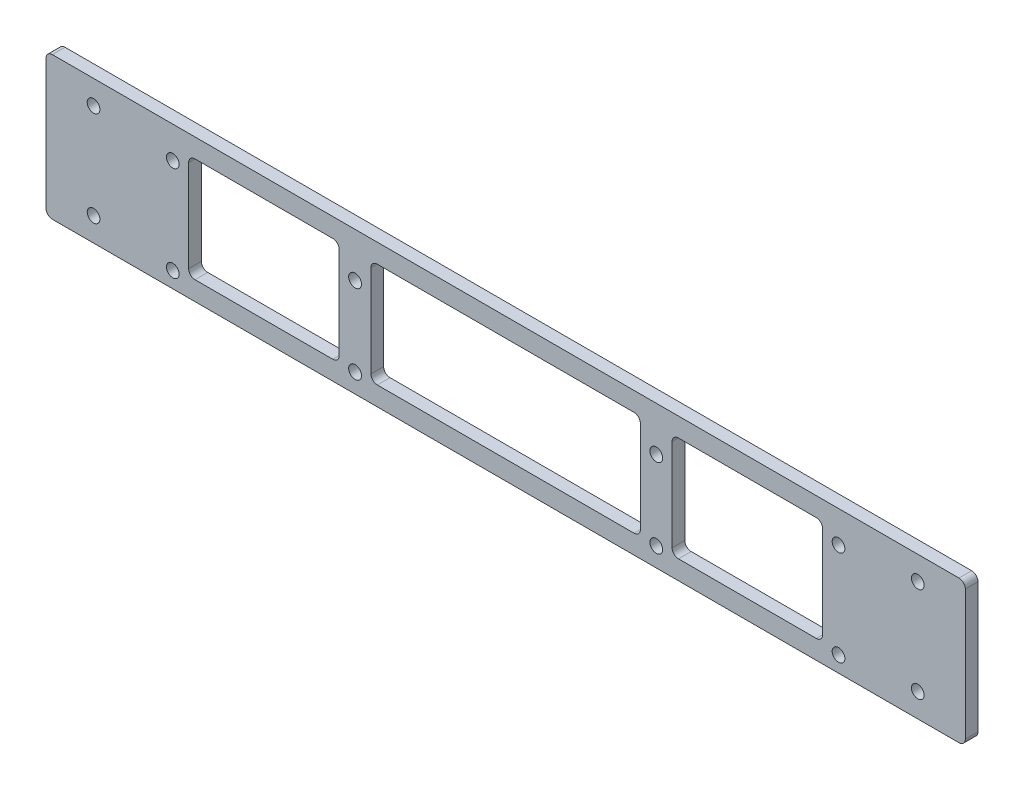
SolidWorks part; units mm, degrees
material "Thornel Mat VMA"
ref_plane "前视基准面" through (0, 0, 0) normal (0, 0, 1) x (1, 0, 0)
ref_plane "上视基准面" through (0, 0, 0) normal (0, 1, 0) x (1, 0, 0)
ref_plane "右视基准面" through (0, 0, 0) normal (1, 0, 0) x (0, 0, -1)
sketch "草图1" plane through (0, 0, 0) normal (0, 0, 1) x (1, 0, 0)
  line L1 (-145, -22.5) -> (145, -22.5)
  line L2 (-145, -22.5) -> (-145, 22.5)
  line L3 (-145, 22.5) -> (145, 22.5)
  line L4 (145, -22.5) -> (145, 22.5)
  line L5 (0, 22.5) -> (0, -22.5) construction
  line L6 (-145, 0) -> (145, 0) construction
  point P0 (0, 0)
  dimension "D1" = 45
  dimension "D2" = 290
extrude "凸台-拉伸1" add sketch "草图1" along normal mid plane 4
sketch "草图3" plane through (0, 0, -2) normal (0, 0, -1) x (-1, 0, 0)
  circle A0 centre (-47.5, 8.5243) radius 1.65 construction
  circle A1 centre (-47.5, -16.4757) radius 1.65 construction
  circle A2 centre (47.5, 8.5243) radius 1.65 construction
  circle A3 centre (47.5, -16.4757) radius 1.65 construction
  circle A4 centre (-47.5, 8.5243) radius 1.65 construction
  circle A5 centre (-47.5, -16.4757) radius 1.65 construction
  circle A6 centre (47.5, 8.5243) radius 1.65 construction
  circle A7 centre (47.5, -16.4757) radius 1.65 construction
  circle A8 centre (-47.5, 8.5243) radius 2.025
  circle A9 centre (-47.5, -16.4757) radius 2.025
  circle A10 centre (47.5, 8.5243) radius 2.025
  circle A11 centre (47.5, -16.4757) radius 2.025
  dimension "D1" = 4.05
extrude "切除-拉伸1" cut sketch "草图3" against normal blind 10
sketch "草图4" plane through (0, 0, -2) normal (0, 0, -1) x (-1, 0, 0)
  line L0 (-130, 22.5) -> (-130, -22.5) construction
  line L1 (-145, 22.5) -> (145, 22.5) construction
  line L2 (145, -22.5) -> (-145, -22.5) construction
  line L3 (-145, -22.5) -> (-145, 22.5) construction
  line L4 (-130, 0) -> (-98.4237, 0) construction
  circle A0 centre (-130, 15) radius 2
  circle A1 centre (-130, -15) radius 2
  dimension "D2" = 4
  dimension "D1" = 15
  dimension "D3" = 30
extrude "切除-拉伸2" cut sketch "草图4" against normal blind 10
mirror "镜向1" about plane through (0, 0, 0) normal (1, 0, 0) of "切除-拉伸2"
sketch "草图5" plane through (0, 0, -2) normal (0, 0, -1) x (-1, 0, 0)
  circle A0 centre (-105, -17.5) radius 2 construction
  circle A1 centre (-105, 12.5) radius 2 construction
  circle A2 centre (-105, -17.5) radius 2
  circle A3 centre (-105, 12.5) radius 2
extrude "切除-拉伸3" cut sketch "草图5" against normal mid plane 70
mirror "镜向2" about plane through (0, 0, 0) normal (1, 0, 0) of "切除-拉伸3"
sketch "草图6" plane through (0, 0, -2) normal (0, 0, -1) x (-1, 0, 0)
  line L0 (-76.25, 0) -> (0, 0) construction
  line L1 (-100, -16.5) -> (-52.5, -16.5)
  line L2 (-100, -16.5) -> (-100, 16.5)
  line L3 (-100, 16.5) -> (-52.5, 16.5)
  line L4 (-52.5, -16.5) -> (-52.5, 16.5)
  line L5 (-76.25, 16.5) -> (-76.25, -16.5) construction
  line L6 (-100, 0) -> (-52.5, 0) construction
  line L7 (145, -22.5) -> (-145, -22.5) construction
  circle A0 centre (-47.5, 8.5243) radius 2.025 construction
  circle A1 centre (-105, 12.5) radius 2 construction
  point P0 (-76.25, 0)
  dimension "D2" = 5
  dimension "D1" = 5
  dimension "D3" = 6
extrude "切除-拉伸4" cut sketch "草图6" against normal mid plane 259
mirror "镜向3" about plane through (0, 0, 0) normal (1, 0, 0) of "切除-拉伸4"
sketch "草图7" plane through (0, 0, -2) normal (0, 0, -1) x (-1, 0, 0)
  line L0 (-52.5, 16.5) -> (-100, 16.5) construction
  line L1 (-42.5, -16.5) -> (42.5, -16.5)
  line L2 (-42.5, -16.5) -> (-42.5, 16.5)
  line L3 (-42.5, 16.5) -> (42.5, 16.5)
  line L4 (42.5, -16.5) -> (42.5, 16.5)
  line L5 (0, 16.5) -> (0, -16.5) construction
  line L6 (-42.5, 0) -> (42.5, 0) construction
  circle A0 centre (-47.5, 8.5243) radius 2.025 construction
  point P0 (0, 0)
  dimension "D1" = 5
extrude "切除-拉伸5" cut sketch "草图7" against normal mid plane 259
fillet "圆角1" radius 2 12 edges at (-52.5, 16.5, 0) (-100, 16.5, 0) (-100, -16.5, 0) (-52.5, -16.5, 0) (52.5, 16.5, 0) (52.5, -16.5, 0) (42.5, -16.5, 0) (42.5, 16.5, 0) (-42.5, 16.5, 0) (-42.5, -16.5, 0) (100, -16.5, 0) (100, 16.5, 0)
fillet "圆角2" radius 2 4 edges at (145, -22.5, 0) (145, 22.5, 0) (-145, 22.5, 0) (-145, -22.5, 0)
